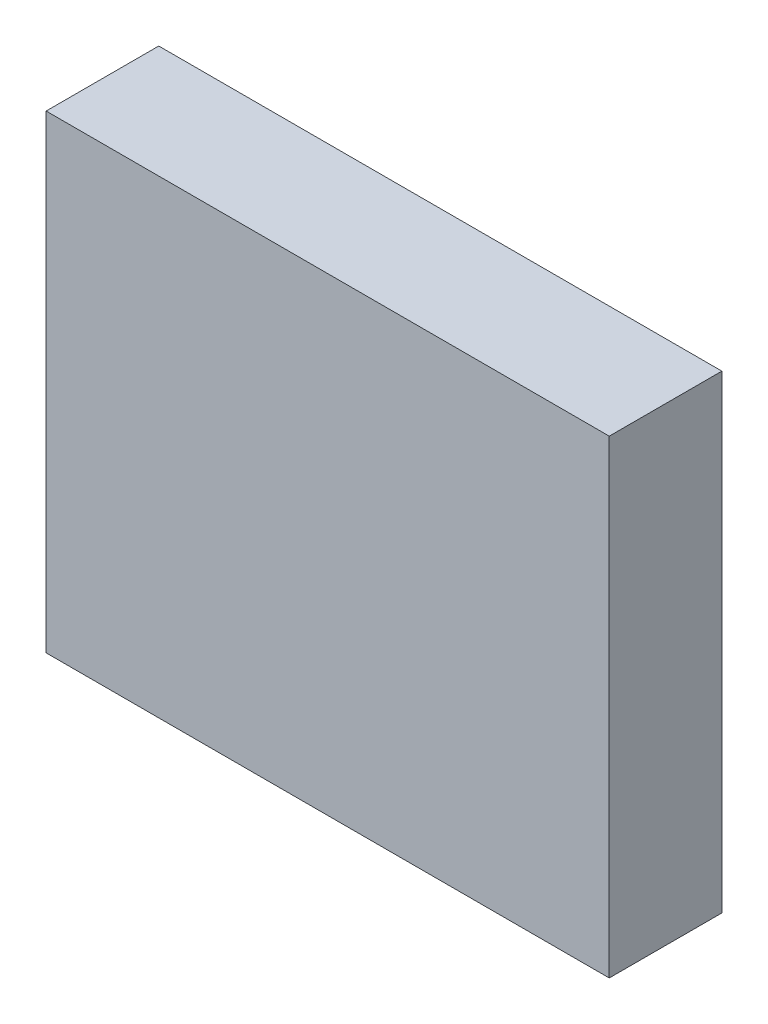
SolidWorks part; units mm, degrees
ref_plane "Front Plane" through (0, 0, 0) normal (0, 0, 1) x (1, 0, 0)
ref_plane "Top Plane" through (0, 0, 0) normal (0, 1, 0) x (1, 0, 0)
ref_plane "Right Plane" through (0, 0, 0) normal (1, 0, 0) x (0, 0, -1)
other "Configuration Table"
sketch "Sketch1" plane through (0, 0, 0) normal (0, 0, 1) x (1, 0, 0)
  line L1 (940, 1680) -> (1240, 1680)
  line L2 (940, 1680) -> (940, 1930)
  line L3 (940, 1930) -> (1240, 1930)
  line L4 (1240, 1680) -> (1240, 1930)
extrude "STORE_sog2_kondenser_1" add sketch "Sketch1" against normal blind 60 from offset 240 separate body
